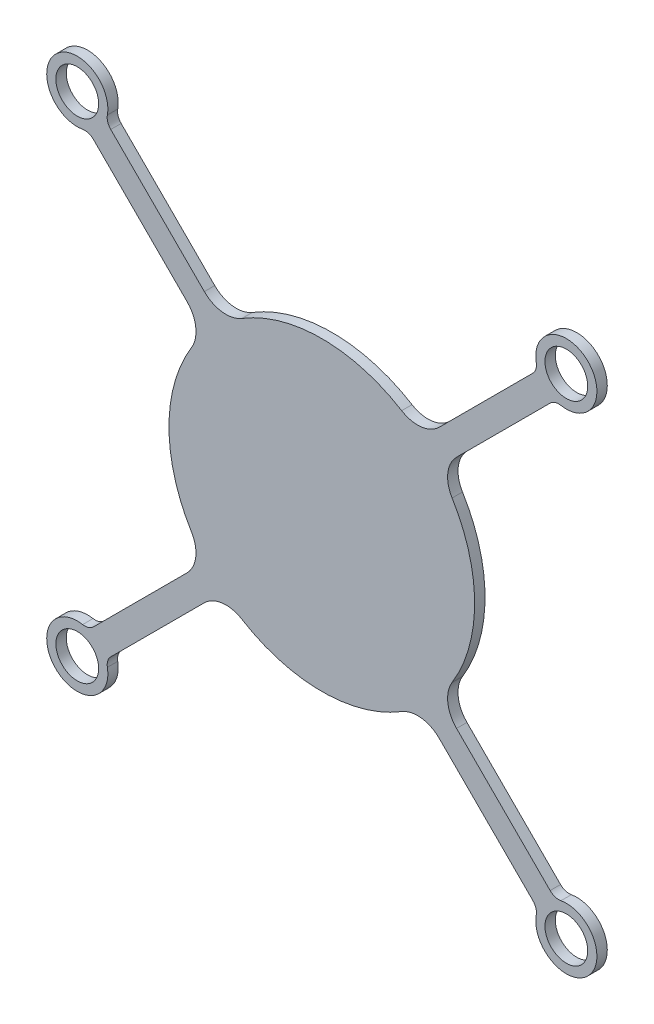
SolidWorks part; units mm, degrees
ref_plane "Front Plane" through (0, 0, 0) normal (0, 0, 1) x (1, 0, 0)
ref_plane "Top Plane" through (0, 0, 0) normal (0, 1, 0) x (1, 0, 0)
ref_plane "Right Plane" through (0, 0, 0) normal (1, 0, 0) x (0, 0, -1)
sketch "Sketch1" plane through (0, 0, 0) normal (0, 0, 1) x (1, 0, 0)
  line L0 (35.3454, -38.1738) -> (16.2068, -19.0352)
  line L1 (38.1738, -35.3454) -> (19.0352, -16.2068)
  line L5 (-38.1738, -35.3454) -> (-19.0352, -16.2068)
  line L6 (-35.3454, -38.1738) -> (-16.2068, -19.0352)
  line L13 (16.2068, 19.0352) -> (35.3454, 38.1738)
  line L19 (-35.3454, 38.1738) -> (-16.2068, 19.0352)
  line L23 (-38.1738, 35.3454) -> (-19.0352, 16.2068)
  line L27 (19.0352, 16.2068) -> (38.1738, 35.3454)
  arc A0 (19.0352, -16.2068) -> (19.0352, 16.2068) centre (0, 0) ccw
  arc A1 (-16.2068, -19.0352) -> (16.2068, -19.0352) centre (0, 0) ccw
  arc A2 (16.2068, 19.0352) -> (-16.2068, 19.0352) centre (0, 0) ccw
  circle A13 centre (-40, 40) radius 3.5
  circle A14 centre (40, 40) radius 3.5
  circle A17 centre (40, -40) radius 3.5
  circle A18 centre (-40, -40) radius 3.5
  arc A21 (38.1738, 35.3454) -> (35.3454, 38.1738) centre (40, 40) ccw
  arc A22 (-35.3454, 38.1738) -> (-38.1738, 35.3454) centre (-40, 40) ccw
  arc A25 (-38.1738, -35.3454) -> (-35.3454, -38.1738) centre (-40, -40) ccw
  arc A26 (35.3454, -38.1738) -> (38.1738, -35.3454) centre (40, -40) ccw
  arc A27 (-19.0352, 16.2068) -> (-19.0352, -16.2068) centre (0, 0) ccw
  point P67 (0, 0)
extrude "Boss-Extrude2" add sketch "Sketch1" along normal blind 1.7
fillet "Fillet1" radius 5 8 edges at (-19.0352, -16.2068, 0.85) (-16.2068, -19.0352, 0.85) (16.2068, -19.0352, 0.85) (19.0352, -16.2068, 0.85) (19.0352, 16.2068, 0.85) (16.2068, 19.0352, 0.85) (-16.2068, 19.0352, 0.85) (-19.0352, 16.2068, 0.85)
fillet "Fillet2" radius 2 8 edges at (38.1738, -35.3454, 0.85) (35.3454, -38.1738, 0.85) (-38.1738, -35.3454, 0.85) (-35.3454, -38.1738, 0.85) (35.3454, 38.1738, 0.85) (38.1738, 35.3454, 0.85) (-35.3454, 38.1738, 0.85) (-38.1738, 35.3454, 0.85)
sketch "Sketch2" plane through (0, 0, 1.7) normal (0, 0, 1) x (1, 0, 0)
  point P1 (0, 0)
